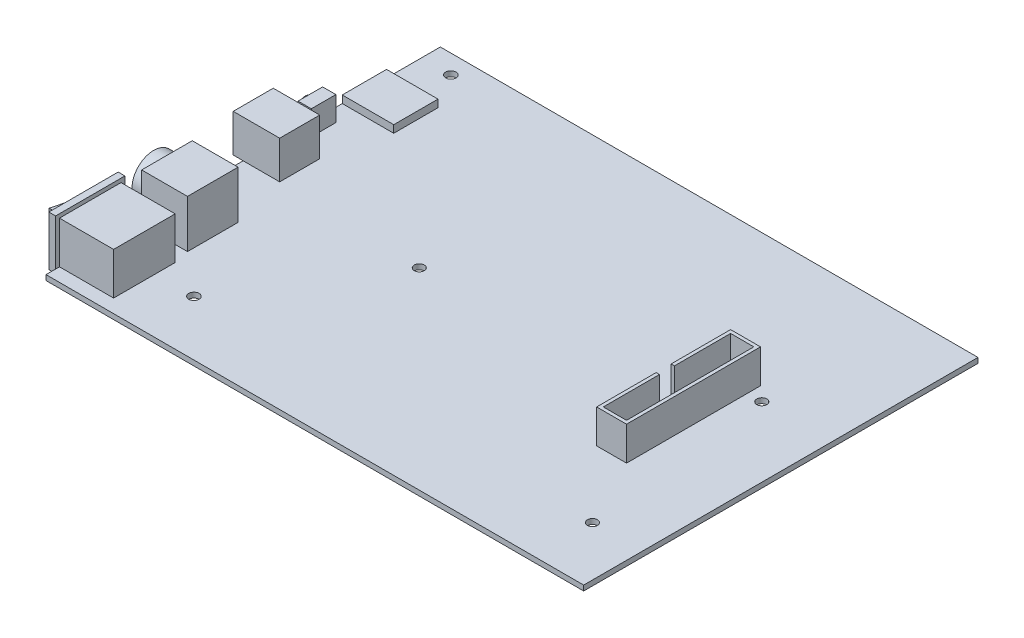
SolidWorks part; units mm, degrees
ref_plane "Front Plane" through (0, 0, 0) normal (0, 0, 1) x (1, 0, 0)
ref_plane "Top Plane" through (0, 0, 0) normal (0, 1, 0) x (1, 0, 0)
ref_plane "Right Plane" through (0, 0, 0) normal (1, 0, 0) x (0, 0, -1)
sketch "Sketch1" plane through (0, 0, 0) normal (0, 1, 0) x (1, 0, 0)
  line L1 (-70.7342, 57.2696) -> (91.1908, 57.2696)
  line L2 (-70.7342, 57.2696) -> (-70.7342, -61.4754)
  line L3 (-70.7342, -61.4754) -> (91.1908, -61.4754)
  line L4 (91.1908, 57.2696) -> (91.1908, -61.4754)
  circle A4 centre (-42.7942, -44.8604) radius 1.55
  circle A5 centre (-61.8442, 51.5546) radius 1.55
  circle A6 centre (70.2058, 13.1396) radius 1.5
  circle A7 centre (-16.2942, -3.5004) radius 1.5
  circle A8 centre (76.2058, -43.8604) radius 1.5
  dimension "D4" = 3.1
  dimension "D6" = 3.1
  dimension "D10" = 3
  dimension "D11" = 3
  dimension "D12" = 3
  dimension "D1" = 161.925
  dimension "D2" = 118.745
extrude "Boss-Extrude1" add sketch "Sketch1" along normal blind 1.56
sketch "Sketch2" plane through (0, 1.56, 0) normal (0, 1, 0) x (1, 0, 0)
  line L0 (-14.8639, -61.4754) -> (-14.8639, -48.1404)
  line L1 (-70.7342, -61.4754) -> (91.1908, -61.4754) construction
  line L2 (7.377, -61.4754) -> (7.377, 34.4096)
  line L3 (37.8642, -61.4754) -> (37.8642, 3.9296)
  line L4 (-14.8639, -48.1404) -> (-70.7342, -48.1404)
  line L5 (-70.7342, 57.2696) -> (-70.7342, -61.4754) construction
  line L6 (37.8642, 3.9296) -> (-70.7342, 3.9296)
  line L7 (7.377, 34.4096) -> (-70.7342, 34.4096)
  line L8 (47.4477, -61.4754) -> (47.4477, -26.5504)
  line L9 (47.4477, -26.5504) -> (-70.7342, -26.5504)
  line L10 (-70.7342, -48.1404) -> (-70.7342, -58.6179)
  line L11 (-70.7342, -26.5504) -> (-70.7342, -18.9304)
  line L12 (-70.7342, -58.6179) -> (-50.7342, -58.6179)
  line L13 (-70.7342, -58.6179) -> (-70.7342, -37.6629)
  line L14 (-70.7342, -37.6629) -> (-50.7342, -37.6629)
  line L15 (-50.7342, -58.6179) -> (-50.7342, -37.6629)
  line L16 (-70.7342, 3.9296) -> (-70.7342, 9.9621)
  line L17 (-70.7342, -18.9304) -> (-55.4342, -18.9304)
  line L18 (-70.7342, -18.9304) -> (-70.7342, -34.1704)
  line L19 (-70.7342, -34.1704) -> (-55.4342, -34.1704)
  line L20 (-55.4342, -18.9304) -> (-55.4342, -34.1704)
  line L21 (-70.7342, 34.4096) -> (-70.7342, 41.0771)
  line L22 (-70.7342, 9.9621) -> (-59.7342, 9.9621)
  line L23 (-70.7342, 9.9621) -> (-70.7342, -2.1029)
  line L24 (-70.7342, -2.1029) -> (-59.7342, -2.1029)
  line L25 (-59.7342, 9.9621) -> (-59.7342, -2.1029)
  line L27 (-70.7342, 41.0771) -> (-55.2342, 41.0771)
  line L28 (-70.7342, 41.0771) -> (-70.7342, 27.7421)
  line L29 (-70.7342, 27.7421) -> (-55.2342, 27.7421)
  line L30 (-55.2342, 41.0771) -> (-55.2342, 27.7421)
  line L31 (-70.7342, -18.9304) -> (-73.2342, -18.9304)
  line L32 (-70.7342, -18.9304) -> (-70.7342, -34.1704)
  line L33 (-70.7342, -34.1704) -> (-73.2342, -34.1704)
  line L34 (-73.2342, -18.9304) -> (-73.2342, -34.1704)
  line L35 (-70.7342, 9.9621) -> (-73.7342, 9.9621)
  line L36 (-70.7342, 9.9621) -> (-70.7342, -2.1029)
  line L37 (-70.7342, -2.1029) -> (-73.7342, -2.1029)
  line L38 (-73.7342, 9.9621) -> (-73.7342, -2.1029)
  line M3 (-70.7342, 57.2696) -> (-70.7342, -61.4754)
  dimension "D1" = 13.335
  dimension "D2" = 95.885
  dimension "D3" = 65.405
  dimension "D4" = 34.925
  dimension "D5" = 10.4775
  dimension "D6" = 20.955
  dimension "D7" = 7.62
  dimension "D8" = 15.24
  dimension "D9" = 6.0325
  dimension "D10" = 12.065
  dimension "D11" = 6.6675
  dimension "D12" = 13.335
  dimension "D13" = 15.3
  dimension "D14" = 2.5
  dimension "D15" = 11
  dimension "D16" = 3
  dimension "D17" = 15.5
  dimension "D18" = 20
extrude "Boss-Extrude2" add sketch "Sketch2" along normal blind 5 contours L4 L15 L14 M3 | L12 L15 L4 M3 | L20 L9 L19 M3 | L20 L17 L9 M3 | L31 L34 L33 M3 | L25 L22 L6 M3 | L35 L38 L37 M3 | L25 L6 L24 M3 | L30 L27 L7 M3 | L30 L7 L29 M3
sketch "Sketch4" plane through (0, 6.56, 0) normal (0, 1, 0) x (1, 0, 0)
  line L0 (-73.2342, -34.1704) -> (-55.4342, -34.1704) construction
  line L1 (-73.2342, -18.9304) -> (-55.4342, -18.9304)
  line L2 (-73.2342, -18.9304) -> (-73.2342, -34.1704)
  line L3 (-73.2342, -34.1704) -> (-55.4342, -34.1704)
  line L4 (-55.4342, -18.9304) -> (-55.4342, -34.1704)
  line L5 (-55.4342, -18.9304) -> (-55.4342, -34.1704) construction
extrude "Boss-Extrude3" add sketch "Sketch4" along normal blind 9.4
sketch "Sketch5" plane through (-73.2342, 0, 0) normal (-1, 0, 0) x (0, 0, 1)
  line L3 (18.9304, 1.56) -> (34.1704, 1.56)
  line L6 (18.9304, 1.56) -> (18.9304, 15.96)
  line L7 (18.9304, 15.96) -> (34.1704, 15.96)
  line L8 (34.1704, 1.56) -> (34.1704, 15.96)
  circle A0 centre (26.5504, 8.76) radius 6.5
  dimension "D1" = 13
extrude "Cut-Extrude1" cut sketch "Sketch5" against normal blind 4
sketch "Sketch7" plane through (0, 6.56, 0) normal (0, 1, 0) x (1, 0, 0)
  line L1 (-70.7342, 27.7421) -> (-55.2342, 27.7421)
  line L2 (-70.7342, 27.7421) -> (-70.7342, 41.0771)
  line L3 (-70.7342, 41.0771) -> (-55.2342, 41.0771)
  line L4 (-55.2342, 27.7421) -> (-55.2342, 41.0771)
extrude "Cut-Extrude3" cut sketch "Sketch7" against normal blind 2.75
sketch "Sketch8" plane through (-70.7342, 0, 0) normal (-1, 0, 0) x (0, 0, 1)
  line L0 (-27.7421, 3.81) -> (-27.9921, 3.81)
  line L1 (-41.0771, 3.81) -> (-27.7421, 3.81) construction
  line L2 (-27.7421, 3.81) -> (-27.7421, 3.56)
  line L3 (-27.7421, 3.81) -> (-27.7421, 1.56) construction
  line L4 (-41.0771, 1.56) -> (-40.8271, 1.56)
  line L5 (-40.8271, 1.56) -> (-40.8271, 1.81)
  line L7 (-27.9921, 3.56) -> (-40.8271, 3.56)
  line L8 (-27.9921, 3.56) -> (-27.9921, 1.81)
  line L9 (-27.9921, 1.81) -> (-40.8271, 1.81)
  line L10 (-40.8271, 3.56) -> (-40.8271, 1.81)
  dimension "D1" = 0.25
  dimension "D2" = 0.25
  dimension "D3" = 0.25
  dimension "D4" = 0.25
extrude "Cut-Extrude4" cut sketch "Sketch8" against normal blind 15 contours L7 L10 L9 L8
sketch "Sketch9" plane through (0, 6.56, 0) normal (0, 1, 0) x (1, 0, 0)
  line L1 (-59.7342, 9.9621) -> (-73.7342, 9.9621)
  line L2 (-59.7342, 9.9621) -> (-59.7342, -2.1029)
  line L3 (-59.7342, -2.1029) -> (-73.7342, -2.1029)
  line L4 (-73.7342, 9.9621) -> (-73.7342, -2.1029)
extrude "Boss-Extrude4" add sketch "Sketch9" along normal blind 6.4
sketch "Sketch10" plane through (-73.7342, 0, 0) normal (-1, 0, 0) x (0, 0, 1)
  line L1 (2.1029, 12.96) -> (1.1029, 12.96)
  line L2 (2.1029, 12.96) -> (2.1029, 10.96)
  line L3 (2.1029, 10.96) -> (1.1029, 10.96)
  line L4 (1.1029, 12.96) -> (1.1029, 10.96)
  line L5 (-9.9621, 1.56) -> (-8.9621, 1.56)
  line L6 (-9.9621, 1.56) -> (-9.9621, 3.56)
  line L7 (-9.9621, 3.56) -> (-8.9621, 3.56)
  line L8 (-8.9621, 1.56) -> (-8.9621, 3.56)
  line L9 (1.1029, 10.96) -> (-8.9621, 10.96)
  line L10 (1.1029, 10.96) -> (1.1029, 3.56)
  line L11 (1.1029, 3.56) -> (-8.9621, 3.56)
  line L12 (-8.9621, 10.96) -> (-8.9621, 3.56)
  dimension "D1" = 1
  dimension "D2" = 2
  dimension "D3" = 1
  dimension "D4" = 2
extrude "Cut-Extrude5" cut sketch "Sketch10" against normal blind 13 contours L9 L12 L11 L10
sketch "Sketch11" plane through (-60.7342, 0, 0) normal (-1, 0, 0) x (0, 0, 1)
  line L0 (-7.7464, 10.96) -> (-7.7464, 10.46)
  line L1 (1.1029, 10.96) -> (-8.9621, 10.96) construction
  line L2 (-8.9621, 7.3344) -> (-8.4621, 7.3344)
  line L3 (-8.9621, 10.96) -> (-8.9621, 3.56) construction
  line L5 (-8.4621, 7.46) -> (0.6079, 7.46)
  line L6 (-8.4621, 7.46) -> (-8.4621, 5.46)
  line L7 (-8.4621, 5.46) -> (0.6079, 5.46)
  line L8 (0.6079, 7.46) -> (0.6079, 5.46)
  dimension "D1" = 0.5
  dimension "D2" = 0.5
  dimension "D3" = 9.07
  dimension "D4" = 2
extrude "Boss-Extrude5" add sketch "Sketch11" along normal blind 13 contours L8 L5 L6 L7
sketch "Sketch12" plane through (0, 6.56, 0) normal (0, 1, 0) x (1, 0, 0)
  line L0 (-70.7342, -58.6179) -> (-71.7342, -58.6179)
  line L1 (-71.7342, -58.6179) -> (-71.7342, -60.1179)
  line L2 (-71.7342, -60.1179) -> (-73.7342, -60.1179)
  line L3 (-70.7342, -37.6629) -> (-71.7342, -37.6629)
  line L4 (-71.7342, -37.6629) -> (-71.7342, -36.1629)
  line L5 (-71.7342, -36.1629) -> (-73.807, -36.1629)
  line L6 (-73.7342, -60.1179) -> (-73.807, -36.1629)
  line L7 (-70.7342, -37.6629) -> (-70.7342, -58.6179)
  dimension "D1" = 1
  dimension "D2" = 1.5
  dimension "D3" = 2
  dimension "D4" = 1
  dimension "D5" = 1.5
extrude "Boss-Extrude6" add sketch "Sketch12" against normal up to surface (5 mm away) up to face at (-45.9311, 1.56, 0.7138)
sketch "Sketch13" plane through (0, 6.56, 0) normal (0, 1, 0) x (1, 0, 0)
  line L0 (-50.7342, -37.6629) -> (-50.7342, -58.6179)
  line L1 (-50.7342, -58.6179) -> (-71.7342, -58.6179)
  line L2 (-71.7342, -58.6179) -> (-71.7342, -60.1179)
  line L3 (-71.7342, -60.1179) -> (-73.7342, -60.1179)
  line L4 (-73.807, -36.1629) -> (-73.7342, -60.1179) construction
  line L5 (-73.7342, -60.1179) -> (-71.7342, -60.1179) construction
  line L6 (-73.7342, -60.1179) -> (-73.807, -36.1629)
  line L7 (-73.807, -36.1629) -> (-71.7342, -36.1629)
  line L8 (-71.7342, -36.1629) -> (-71.7342, -37.6629)
  line L9 (-71.7342, -37.6629) -> (-50.7342, -37.6629)
extrude "Boss-Extrude8" add sketch "Sketch13" along normal blind 4
sketch "Sketch38" plane through (0, 1.56, 0) normal (0, 1, 0) x (1, 0, 0)
  line L1 (-48.843, -34.9905) -> (-79.9366, -34.9905)
  line L2 (-48.843, -34.9905) -> (-48.843, -60.5949)
  line L3 (-48.843, -60.5949) -> (-79.9366, -60.5949)
  line L4 (-79.9366, -34.9905) -> (-79.9366, -60.5949)
extrude "Cut-Extrude14" cut sketch "Sketch38" along normal blind 10
sketch "Sketch39" plane through (0, 1.56, 0) normal (0, 1, 0) x (1, 0, 0)
  line L0 (-70.7342, -61.4754) -> (-70.7342, -57.4154)
  line L1 (-70.7342, -2.1029) -> (-70.7342, -61.4754) construction
  line L3 (-70.7342, -57.4154) -> (-54.4342, -57.4154)
  line L4 (-70.7342, -57.4154) -> (-70.7342, -38.8754)
  line L5 (-70.7342, -38.8754) -> (-54.4342, -38.8754)
  line L6 (-54.4342, -57.4154) -> (-54.4342, -38.8754)
  line M2 (-70.7342, -2.1029) -> (-70.7342, -61.4754)
  dimension "D1" = 4.06
  dimension "D2" = 18.54
  dimension "D3" = 16.3
extrude "Boss-Extrude9" add sketch "Sketch39" along normal blind 12.7 contours L3 L6 L5 M2
sketch "Sketch40" plane through (-70.7342, 0, 0) normal (-1, 0, 0) x (0, 0, 1)
  line L0 (38.8754, 14.26) -> (38.8754, 1.56) construction
  line L1 (38.8754, 14.26) -> (37.7154, 14.26)
  line L2 (38.8754, 14.26) -> (38.8754, 15.42)
  line L3 (38.8754, 15.42) -> (37.7154, 15.42)
  line L4 (37.7154, 14.26) -> (37.7154, 15.42)
  line L5 (38.8754, 14.26) -> (57.4154, 14.26) construction
  line L7 (57.4154, 1.56) -> (58.5754, 1.56)
  line L8 (57.4154, 1.56) -> (57.4154, 0.4)
  line L9 (57.4154, 0.4) -> (58.5754, 0.4)
  line L10 (58.5754, 1.56) -> (58.5754, 0.4)
  line L11 (37.7154, 15.42) -> (58.5754, 15.42)
  line L12 (37.7154, 15.42) -> (37.7154, 0.4)
  line L13 (37.7154, 0.4) -> (58.5754, 0.4)
  line L14 (58.5754, 15.42) -> (58.5754, 0.4)
  line M5 (38.8754, 1.56) -> (2.1029, 1.56)
  line M15 (61.4754, 1.56) -> (57.4154, 1.56)
  line M16 (57.4154, 1.56) -> (57.4154, 14.26)
  line M17 (57.4154, 14.26) -> (38.8754, 14.26)
  line M18 (38.8754, 14.26) -> (38.8754, 1.56)
  dimension "D1" = 1.16
  dimension "D2" = 1.16
  dimension "D3" = 1.16
  dimension "D4" = 1.16
extrude "Boss-Extrude10" add sketch "Sketch40" along normal blind 2.03 contours L4 L1 L2 L3 | L14 L11 L2 M17 M16 M15 | L1 L12 M5 M18 | L12 L13 L8 M16 M17 M18 M5 | L10 L8 L9 M15
sketch "Sketch41" plane through (-72.7642, 0, 0) normal (-1, 0, 0) x (0, 0, 1)
  line L1 (37.7154, 15.42) -> (41.3104, 15.42)
  line L2 (37.7154, 15.42) -> (37.7154, 12.865)
  line L3 (37.7154, 12.865) -> (41.3104, 12.865)
  line L4 (41.3104, 15.42) -> (41.3104, 12.865)
  line L5 (41.3104, 12.865) -> (54.9804, 12.865)
  line L6 (41.3104, 12.865) -> (41.3104, 2.955)
  line L7 (41.3104, 2.955) -> (54.9804, 2.955)
  line L8 (54.9804, 12.865) -> (54.9804, 2.955)
  dimension "D1" = 2.555
  dimension "D2" = 3.595
  dimension "D3" = 13.67
  dimension "D4" = 9.91
extrude "Boss-Extrude11" add sketch "Sketch41" along normal blind 3.51 contours L8 L5 L6 L7
sketch "Sketch42" plane through (0, 12.865, 0) normal (0, 1, 0) x (1, 0, 0)
  line L0 (-72.7642, -41.3104) -> (-76.2742, -54.9804)
  line L1 (-76.2742, -54.9804) -> (-76.2742, -41.3104)
  line L2 (-76.2742, -41.3104) -> (-72.7642, -41.3104)
extrude "Cut-Extrude15" cut sketch "Sketch42" against normal through all
sketch "Sketch43" plane through (0, 1.56, 0) normal (0, 1, 0) x (1, 0, 0)
  line L0 (65.8458, -23.2304) -> (65.8458, 17.1096)
  line L1 (65.8458, -23.2304) -> (56.8458, -23.2304)
  line L2 (56.8458, -23.2304) -> (56.8458, 17.1096)
  line L3 (65.8458, 17.1096) -> (56.8458, 17.1096)
  line L4 (56.8458, -3.0604) -> (65.8458, -3.0604) construction
  point P6 (61.3458, -3.0604)
  dimension "D1" = 40.34
  dimension "D2" = 9
extrude "Boss-Extrude12" add sketch "Sketch43" along normal blind 10.16
sketch "Sketch44" plane through (0, 11.72, 0) normal (0, 1, 0) x (1, 0, 0)
  line L0 (57.8458, -0.8104) -> (56.8458, -0.8104)
  line L1 (56.8458, -0.8104) -> (56.8458, -5.3104)
  line L2 (56.8458, -5.3104) -> (57.8458, -5.3104)
  line L3 (64.8458, 16.1096) -> (57.8458, 16.1096)
  line L4 (57.8458, 16.1096) -> (57.8458, -0.8104)
  line L5 (57.8458, -22.2304) -> (64.8458, -22.2304)
  line L6 (64.8458, -22.2304) -> (64.8458, 16.1096)
  line L7 (57.8458, -5.3104) -> (57.8458, -22.2304)
  line L8 (56.8458, -3.0604) -> (65.8458, -3.0604) construction
  line L9 (65.8458, -23.2304) -> (65.8458, 17.1096) construction
  line L10 (56.8458, 17.1096) -> (56.8458, -23.2304) construction
  dimension "D1" = 4.5
  dimension "D2" = 38.34
  dimension "D3" = 7
  dimension "D4" = 1
extrude "Cut-Extrude16" cut sketch "Sketch44" against normal offset from surface (8.66 mm away) 1.5 up to face at (-47.987, 1.56, 5.9503)
sketch "Sketch46" plane through (0, 0, 0) normal (0, -1, 0) x (1, 0, 0)
  line L0 (-70.7342, -57.2696) -> (-40.7342, -57.2696) construction
  line L1 (91.1908, -57.2696) -> (-70.7342, -57.2696) construction
  line L2 (-40.7342, -57.2696) -> (-40.7342, -52.2696) construction
  line L3 (-70.7342, -57.2696) -> (-70.7342, -24.2696) construction
  line L4 (-40.7342, -52.2696) -> (79.2658, -52.2696)
  line L5 (-40.7342, -52.2696) -> (-40.7342, -42.7696)
  line L6 (-40.7342, -42.7696) -> (79.2658, -42.7696)
  line L7 (79.2658, -52.2696) -> (79.2658, -42.7696)
  line L8 (-70.7342, -57.2696) -> (-70.7342, 61.4754) construction
  line L9 (-63.7342, -14.2696) -> (-45.7342, -14.2696) construction
  line L10 (-70.7342, -24.2696) -> (-63.7342, -24.2696)
  line L11 (-70.7342, -24.2696) -> (-70.7342, -14.2696)
  line L12 (-70.7342, -14.2696) -> (-63.7342, -14.2696)
  line L13 (-63.7342, -24.2696) -> (-63.7342, -14.2696)
  line L14 (-70.7342, -57.2696) -> (-70.7342, -0.7696) construction
  line L15 (-45.7342, -14.2696) -> (-37.9606, -14.2696)
  line L16 (-45.7342, -14.2696) -> (-45.7342, -24.2696)
  line L17 (-45.7342, -24.2696) -> (-37.9606, -24.2696)
  line L18 (-37.9606, -14.2696) -> (-37.9606, -24.2696)
  line L19 (-70.7342, -11.132) -> (-58.7342, -11.132)
  line L20 (-70.7342, -11.132) -> (-70.7342, 6.868)
  line L21 (-70.7342, 6.868) -> (-58.7342, 6.868)
  line L22 (-58.7342, -11.132) -> (-58.7342, 6.868)
  line L23 (-70.7342, -0.7696) -> (-58.7342, -0.7696) construction
  line L25 (-48.5182, -0.7696) -> (-41.5182, -0.7696)
  line L26 (-48.5182, -0.7696) -> (-48.5182, 1.409)
  line L27 (-48.5182, 1.409) -> (-41.5182, 1.409)
  line L28 (-41.5182, -0.7696) -> (-41.5182, 1.409)
  dimension "D1" = 30
  dimension "D2" = 5
  dimension "D3" = 9.5
  dimension "D4" = 120
  dimension "D5" = 33
  dimension "D6" = 10
  dimension "D7" = 7
  dimension "D8" = 18
  dimension "D9" = 12
  dimension "D10" = 18
  dimension "D11" = 56.5
  dimension "D12" = 12
  dimension "D13" = 7
extrude "Boss-Extrude14" add sketch "Sketch46" along normal blind 3
sketch "Sketch47" plane through (-73.7342, 0, 0) normal (-1, 0, 0) x (0, 0, 1)
  line L0 (-3.9296, 10.96) -> (-6.9296, 10.96) construction
  line L1 (1.1029, 10.96) -> (-8.9621, 10.96) construction
  line L2 (1.1029, 10.96) -> (-8.9621, 10.96) construction
  line L3 (-6.9296, 10.96) -> (-8.9621, 8.9275)
  line L4 (-8.9621, 10.96) -> (-8.9621, 3.56) construction
  line L5 (-8.9621, 8.9275) -> (-8.9621, 10.96)
  line L6 (-8.9621, 10.96) -> (-6.9296, 10.96)
  line L7 (-3.9296, 10.96) -> (-0.9296, 10.96) construction
  line L8 (-0.9296, 10.96) -> (1.1029, 8.9275)
  line L9 (1.1029, 10.96) -> (1.1029, 3.56) construction
  line L10 (1.1029, 8.9275) -> (1.1029, 10.96)
  line L11 (1.1029, 10.96) -> (-0.9296, 10.96)
  dimension "D1" = 3
  dimension "D2" = 3
extrude "Boss-Extrude15" add sketch "Sketch47" against normal up to surface (13 mm away) up to face at (-60.7342, 6.46, -3.9271)
sketch "Sketch49" plane through (0, 1.56, 0) normal (0, 1, 0) x (1, 0, 0)
  line L0 (0, -61.4754) -> (0, 18.1246) construction
  line L1 (0, 18.1246) -> (-70.7342, 18.1246) construction
  line L2 (-70.7342, 21.8246) -> (-66.7342, 21.8246)
  line L3 (-70.7342, 21.8246) -> (-70.7342, 14.4246)
  line L4 (-70.7342, 14.4246) -> (-66.7342, 14.4246)
  line L5 (-66.7342, 21.8246) -> (-66.7342, 14.4246)
  line L6 (-70.7342, -61.4754) -> (91.1908, -61.4754) construction
  line L7 (-70.7342, 27.7421) -> (-70.7342, 9.9621) construction
  dimension "D1" = 79.6
  dimension "D2" = 7.4
  dimension "D3" = 4
  dimension "D4" = 70.7342
extrude "Boss-Extrude16" add sketch "Sketch49" along normal blind 7.31
sketch "Sketch50" plane through (-70.7342, 0, 0) normal (-1, 0, 0) x (0, 0, 1)
  line L0 (-14.4246, 8.87) -> (-14.4246, 2.87) construction
  line L1 (-14.4246, 8.87) -> (-14.4246, 1.56) construction
  line L2 (-14.4246, 2.87) -> (-21.8246, 8.87) construction
  circle A0 centre (-18.1246, 5.87) radius 1.75
  dimension "D2" = 3.5
  dimension "D1" = 6
extrude "Boss-Extrude17" add sketch "Sketch50" along normal blind 1.5
